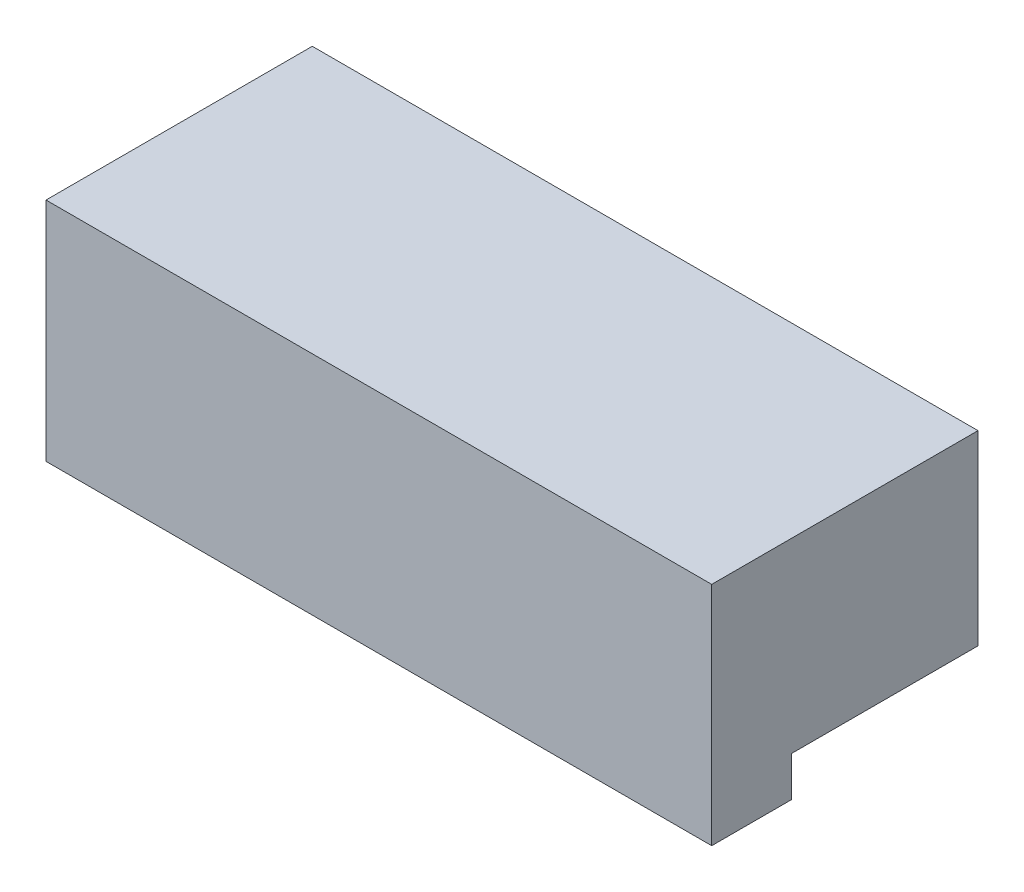
SolidWorks part; units mm, degrees
ref_plane "Plan de face" through (0, 0, 0) normal (0, 0, 1) x (1, 0, 0)
ref_plane "Plan de dessus" through (0, 0, 0) normal (0, 1, 0) x (1, 0, 0)
ref_plane "Plan de droite" through (0, 0, 0) normal (1, 0, 0) x (0, 0, -1)
sketch "Esquisse1" plane through (0, 0, 0) normal (0, 0, 1) x (1, 0, 0)
  line L1 (-15.807, -0.5935) -> (9.193, -0.5935)
  line L2 (-15.807, -0.5935) -> (-15.807, -7.5935)
  line L3 (-15.807, -7.5935) -> (9.193, -7.5935)
  line L4 (9.193, -0.5935) -> (9.193, -7.5935)
  dimension "D1" = 25
  dimension "D2" = 7
extrude "Boss.-Extru.1" add sketch "Esquisse1" along normal blind 10
sketch "Esquisse2" plane through (0, -7.5935, 0) normal (0, -1, 0) x (1, 0, 0)
  line L0 (9.193, 10) -> (9.193, 0) construction
  line L1 (-15.807, 10) -> (9.193, 10)
  line L2 (-15.807, 10) -> (-15.807, 7)
  line L3 (-15.807, 7) -> (9.193, 7)
  line L4 (9.193, 10) -> (9.193, 7)
  dimension "D1" = 3
extrude "Boss.-Extru.2" add sketch "Esquisse2" along normal blind 1.5
